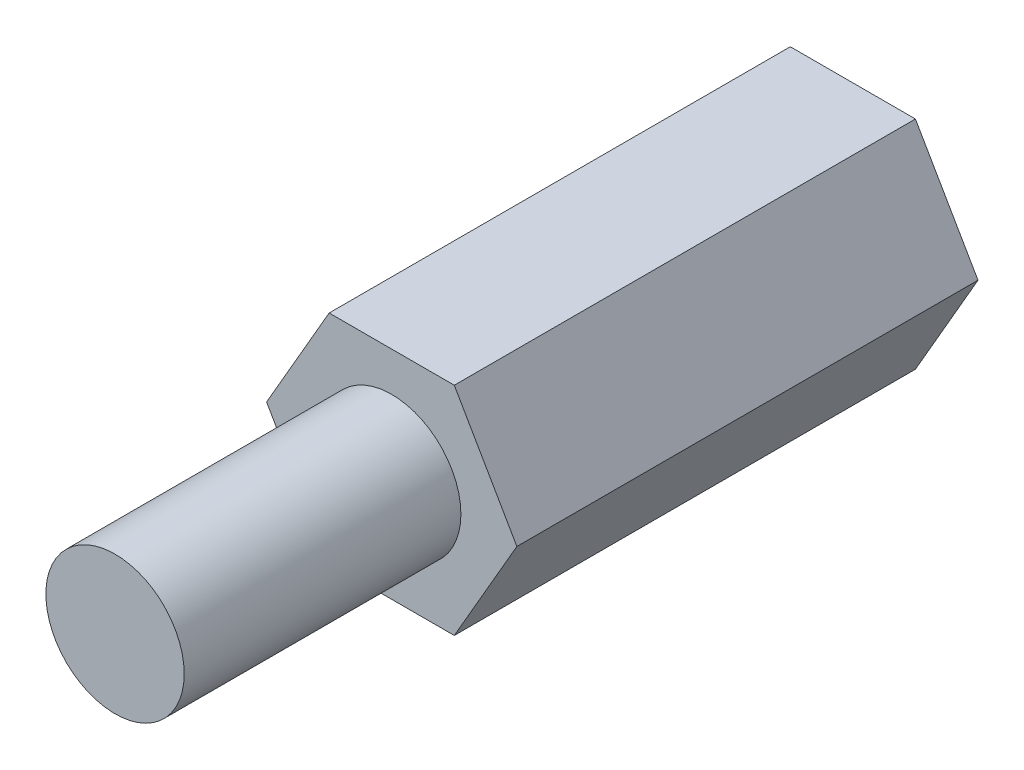
SolidWorks part; units mm, degrees
ref_plane "前视基准面" through (0, 0, 0) normal (0, 0, 1) x (1, 0, 0)
ref_plane "上视基准面" through (0, 0, 0) normal (0, 1, 0) x (1, 0, 0)
ref_plane "右视基准面" through (0, 0, 0) normal (1, 0, 0) x (0, 0, -1)
sketch "草图1" plane through (0, 0, 0) normal (0, 0, 1) x (1, 0, 0)
  line L1 (2.7135, 0) -> (1.3568, 2.35)
  line L2 (1.3568, 2.35) -> (-1.3568, 2.35)
  line L3 (-1.3568, 2.35) -> (-2.7135, 0)
  line L4 (-2.7135, 0) -> (-1.3568, -2.35)
  line L5 (-1.3568, -2.35) -> (1.3568, -2.35)
  line L6 (1.3568, -2.35) -> (2.7135, 0)
  circle A0 centre (0, 0) radius 2.35 construction
  point P1 (-2.0352, -1.175)
  dimension "D1" = 4.7
extrude "凸台-拉伸1" add sketch "草图1" along normal blind 10
sketch "草图2" plane through (0, 0, 10) normal (0, 0, 1) x (1, 0, 0)
  circle A0 centre (0, 0) radius 1.5
  dimension "D1" = 3
extrude "凸台-拉伸2" add sketch "草图2" along normal blind 6
sketch "草图3" plane through (0, 0, 0) normal (0, 0, -1) x (-1, 0, 0)
  circle A0 centre (0, 0) radius 1.5
  dimension "D1" = 3
extrude "切除-拉伸1" cut sketch "草图3" against normal blind 6
